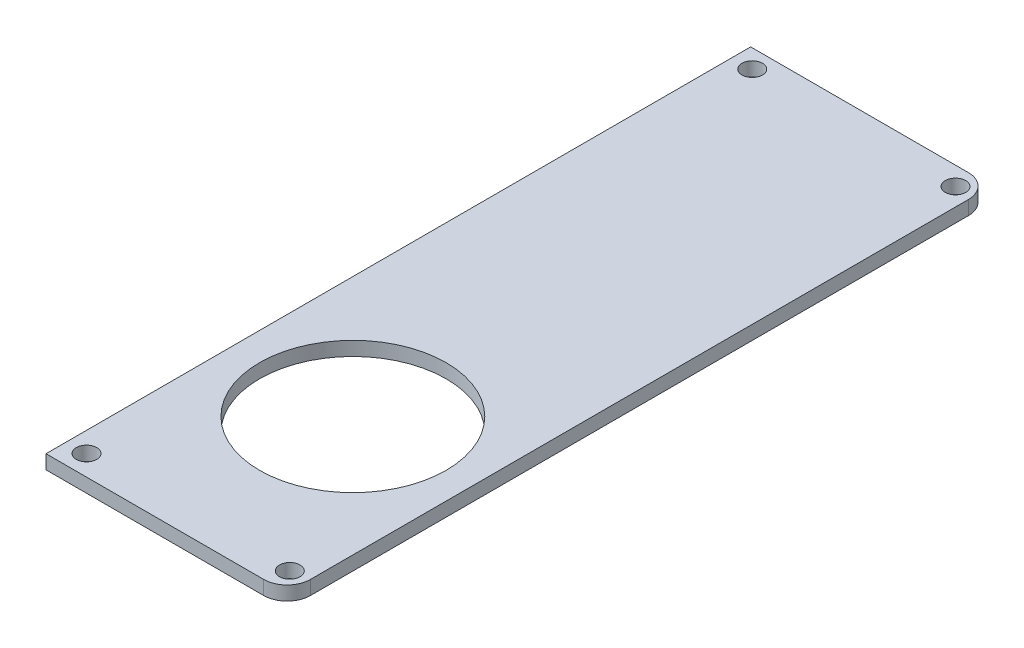
SolidWorks part; units mm, degrees
material "Acrylic (Medium-high impact)"
ref_plane "Front Plane" through (0, 0, 0) normal (0, 0, 1) x (1, 0, 0)
ref_plane "Top Plane" through (0, 0, 0) normal (0, 1, 0) x (1, 0, 0)
ref_plane "Right Plane" through (0, 0, 0) normal (1, 0, 0) x (0, 0, -1)
sketch "Sketch1" plane through (0, 0, 0) normal (0, 1, 0) x (1, 0, 0)
  line L0 (-12.92, 37.765) -> (10.42, 37.765)
  line L1 (-14.42, -39.265) -> (14.42, -39.265) construction
  line L2 (-14.42, -39.265) -> (-14.42, 39.265) construction
  line L3 (-14.42, 39.265) -> (14.42, 39.265) construction
  line L4 (14.42, -39.265) -> (14.42, 39.265) construction
  line L5 (-14.42, -39.265) -> (14.42, 39.265) construction
  line L6 (-14.42, 39.265) -> (14.42, -39.265) construction
  line L7 (12.92, -35.265) -> (12.92, 35.265)
  line L8 (-12.92, -37.765) -> (10.42, -37.765)
  line L9 (-12.92, -37.765) -> (-12.92, 37.765)
  line L10 (14.42, 39.265) -> (11.02, 39.265) construction
  line L11 (11.02, 39.265) -> (11.02, 35.785) construction
  line L12 (11.02, 35.785) -> (-10.77, 35.785) construction
  line L13 (14.42, -39.265) -> (11.02, -39.265) construction
  line L14 (11.02, -39.265) -> (11.02, -35.575) construction
  line L15 (11.02, -35.575) -> (-10.77, -35.575) construction
  line L16 (-12.92, -37.765) -> (12.92, -37.765) construction
  line L17 (12.92, -37.765) -> (12.92, 37.765) construction
  line L18 (-12.92, 37.765) -> (12.92, 37.765) construction
  circle A0 centre (11.02, 35.785) radius 1.1
  circle A1 centre (-10.77, 35.785) radius 1.1
  circle A2 centre (-10.77, -35.575) radius 1.1
  circle A3 centre (11.02, -35.575) radius 1.1
  circle A4 centre (0.07, -17.865) radius 10
  arc A5 (10.42, -37.765) -> (12.92, -35.265) centre (10.42, -35.265) ccw
  arc A6 (12.92, 35.265) -> (10.42, 37.765) centre (10.42, 35.265) ccw
  point P0 (0, 0)
  point P24 (2.5568, -19.1259)
  dimension "D10" = 2.2
  dimension "D11" = 2.2
  dimension "D12" = 2.2
  dimension "D13" = 2.2
  dimension "D16" = 20
  dimension "D17" = 2.5
  dimension "D1" = 28.84
  dimension "D2" = 78.53
  dimension "D4" = 3.4
  dimension "D5" = 3.48
  dimension "D6" = 21.79
  dimension "D7" = 3.4
  dimension "D8" = 3.69
  dimension "D9" = 21.79
  dimension "D14" = 14.35
  dimension "D15" = 21.4
  dimension "D3" = 1.5
extrude "Boss-Extrude2" add sketch "Sketch1" along normal blind 1.5
